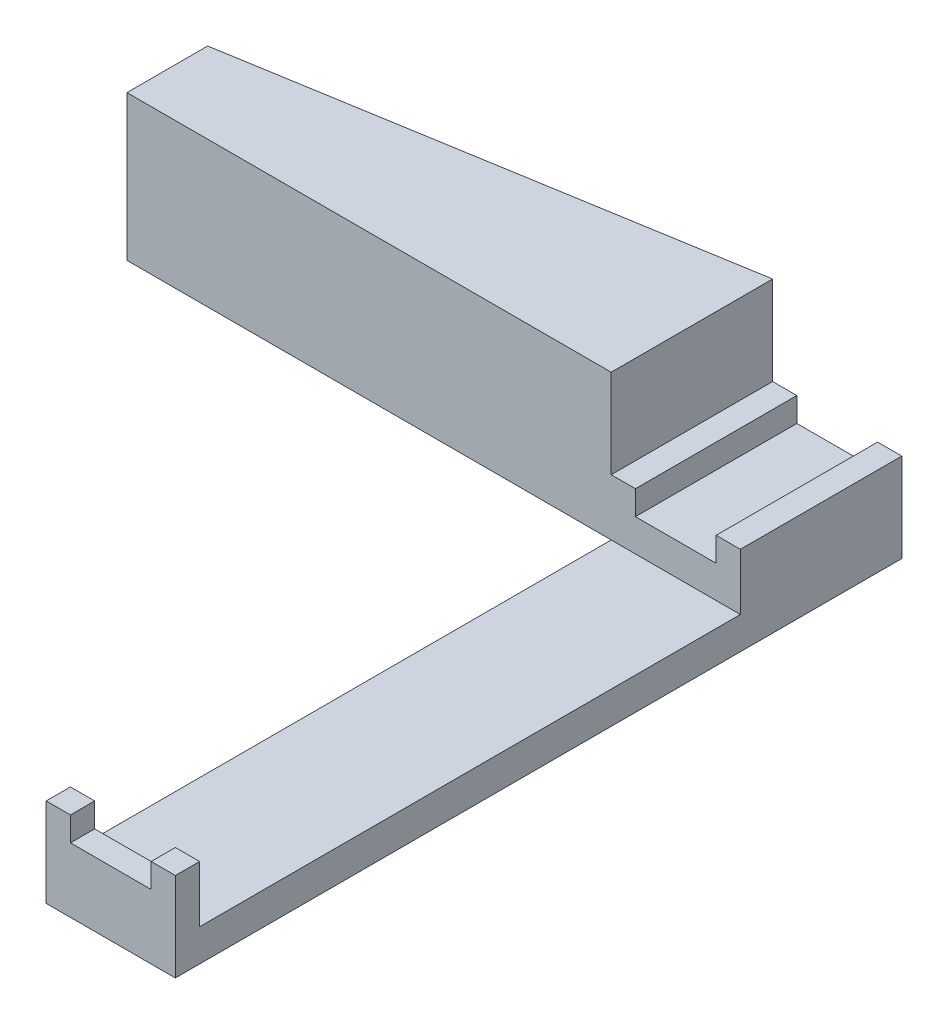
SolidWorks part; units mm, degrees
ref_plane "Front Plane" through (0, 0, 0) normal (0, 0, 1) x (1, 0, 0)
ref_plane "Top Plane" through (0, 0, 0) normal (0, 1, 0) x (1, 0, 0)
ref_plane "Right Plane" through (0, 0, 0) normal (1, 0, 0) x (0, 0, -1)
sketch "Sketch1" plane through (0, 0, 0) normal (0, 1, 0) x (1, 0, 0)
  line L0 (0, 0) -> (30, 0)
  line L1 (30, 0) -> (30, -35)
  line L2 (30, -35) -> (38, -35)
  line L3 (38, -35) -> (38, 10)
  line L4 (38, 10) -> (30, 10)
  line L5 (30, 10) -> (0, 5)
  line L6 (0, 5) -> (0, 0)
  point P6 (0, 2.5)
  dimension "D1" = 8
  dimension "D2" = 45
  dimension "D3" = 30
  dimension "D4" = 5
  dimension "D5" = 10
extrude "Boss-Extrude1" add sketch "Sketch1" along normal blind 12
sketch "Sketch2" plane through (0, 12, 0) normal (0, 1, 0) x (1, 0, 0)
  line L0 (0, 0) -> (30, 0) construction
  line L1 (30, 0) -> (38, 0)
  line L2 (30, 0) -> (30, -33.5)
  line L3 (30, -33.5) -> (38, -33.5)
  line L4 (38, 0) -> (38, -33.5)
  line L5 (30, 0) -> (30, -35) construction
  line L6 (38, -35) -> (38, 10) construction
  line L7 (30, -35) -> (38, -35) construction
  dimension "D1" = 1.5
extrude "Cut-Extrude1" cut sketch "Sketch2" against normal blind 10
sketch "Sketch3" plane through (0, 12, 0) normal (0, 1, 0) x (1, 0, 0)
  line L1 (30, 10) -> (38, 10)
  line L2 (30, 10) -> (30, -35)
  line L3 (30, -35) -> (38, -35)
  line L4 (38, 10) -> (38, -35)
extrude "Cut-Extrude2" cut sketch "Sketch3" against normal blind 6.5
sketch "Sketch4" plane through (0, 5.5, 0) normal (0, 1, 0) x (1, 0, 0)
  line L0 (38, 10) -> (30, 10) construction
  line L1 (31.5, 10) -> (36.5, 10)
  line L2 (31.5, 10) -> (31.5, 0)
  line L3 (31.5, 0) -> (36.5, 0)
  line L4 (36.5, 10) -> (36.5, 0)
  line L5 (38, 0) -> (30, 0) construction
  line L6 (38, 0) -> (38, 10) construction
  dimension "D1" = 5
  dimension "D2" = 1.5
extrude "Cut-Extrude3" cut sketch "Sketch4" against normal blind 1.5
sketch "Sketch5" plane through (0, 5.5, 0) normal (0, 1, 0) x (1, 0, 0)
  line L0 (38, -33.5) -> (30, -33.5) construction
  line L1 (31.5, -33.5) -> (36.5, -33.5)
  line L2 (31.5, -33.5) -> (31.5, -35)
  line L3 (31.5, -35) -> (36.5, -35)
  line L4 (36.5, -33.5) -> (36.5, -35)
  line L5 (30, -35) -> (38, -35) construction
  line L6 (30, -33.5) -> (30, -35) construction
  dimension "D1" = 5
  dimension "D2" = 1.5
extrude "Cut-Extrude4" cut sketch "Sketch5" against normal blind 1.5
sketch "Sketch6" plane through (0, 0, 0) normal (0, -1, 0) x (1, 0, 0)
  line L0 (0, 0) -> (30, 0)
  line L1 (30, 0) -> (30, -10)
  line L2 (30, -10) -> (0, -5)
  line L3 (0, -5) -> (0, 0)
extrude "Cut-Extrude5" cut sketch "Sketch6" against normal blind 2
sketch "Sketch7" plane through (0, 12, 0) normal (0, 1, 0) x (1, 0, 0)
  line L0 (0, 5) -> (30, 10)
  line L1 (30, 10) -> (0, 5) construction
  line L2 (30, 10) -> (30, 0)
  line L3 (30, 0) -> (0, 0)
  line L4 (0, 0) -> (0, 5)
  point P7 (0, 0)
extrude "Cut-Extrude7" cut sketch "Sketch7" against normal blind 1
sketch "Sketch9" plane through (0, 11, 0) normal (0, 1, 0) x (1, 0, 0)
  line L0 (0, 5) -> (30, 10)
  line L1 (30, 10) -> (30, 3)
  line L2 (30, 10) -> (30, 0) construction
  line L3 (30, 3) -> (0, 3)
  line L4 (0, 5) -> (0, 0) construction
  line L5 (0, 3) -> (0, 5)
  line L6 (0, 0) -> (30, 0) construction
  dimension "D1" = 3
extrude "Cut-Extrude8" [suppressed] cut sketch "Sketch9" against normal blind 4
sketch "Sketch10" plane through (0, 2, 0) normal (0, -1, 0) x (1, 0, 0)
  line L0 (0, -5) -> (30, -10)
  line L1 (30, -10) -> (30, -3)
  line L2 (30, -10) -> (30, 35) construction
  line L3 (30, -3) -> (0, -3)
  line L4 (0, 0) -> (0, -5) construction
  line L5 (0, -3) -> (0, -5)
  line L6 (30, 0) -> (0, 0) construction
  dimension "D1" = 3
extrude "Cut-Extrude9" cut sketch "Sketch10" against normal blind 3
